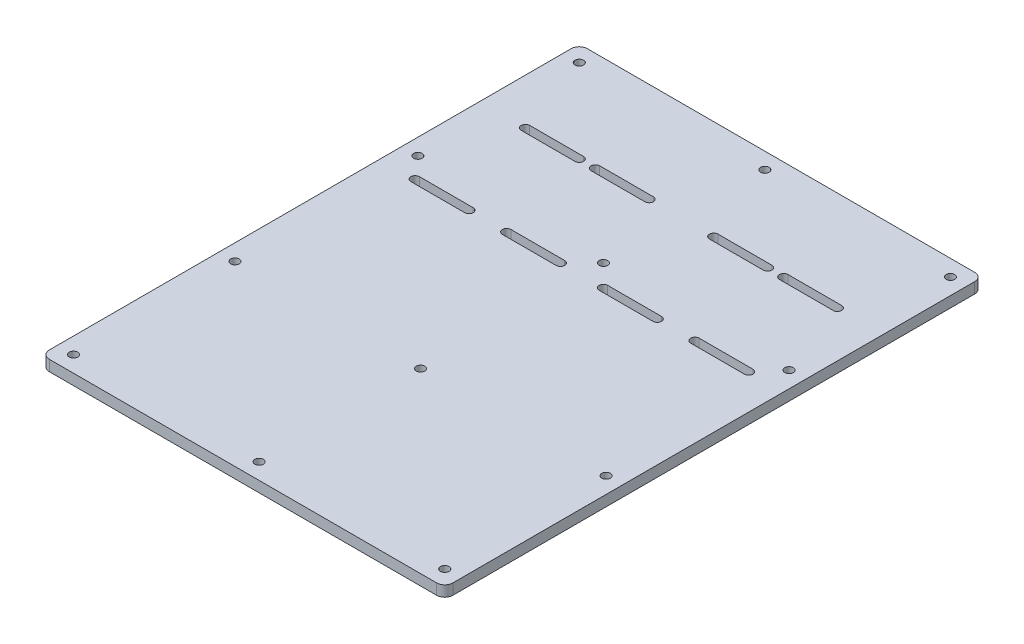
SolidWorks part; units mm, degrees
ref_plane "Front" through (0, 0, 0) normal (0, 0, 1) x (1, 0, 0)
ref_plane "Top" through (0, 0, 0) normal (0, 1, 0) x (1, 0, 0)
ref_plane "Right" through (0, 0, 0) normal (1, 0, 0) x (0, 0, -1)
sketch "Эскиз1" plane through (0, 0, 0) normal (0, 1, 0) x (1, 0, 0)
  line L1 (-72, 100) -> (72, 100)
  line L2 (-75, 97) -> (-75, -97)
  line L3 (-72, -100) -> (72, -100)
  line L4 (75, 97) -> (75, -97)
  line L5 (-75, 100) -> (75, -100) construction
  line L6 (-75, -100) -> (75, 100) construction
  arc A0 (75, -97) -> (72, -100) centre (72, -97) cw
  arc A1 (-72, -100) -> (-75, -97) centre (-72, -97) cw
  arc A2 (75, 97) -> (72, 100) centre (72, 97) ccw
  arc A3 (-72, 100) -> (-75, 97) centre (-72, 97) ccw
  point P0 (0, 0)
  dimension "D1" = 3
extrude "Бобышка-Вытянуть1" add sketch "Эскиз1" along normal blind 4
sketch "Эскиз2" plane through (0, 4, 0) normal (0, 1, 0) x (1, 0, 0)
  line L0 (-32, 64.5875) -> (-12, 64.5875)
  line L1 (0, 100) -> (0, -100) construction
  line L2 (72, 100) -> (-72, 100) construction
  line L3 (-72, -100) -> (72, -100) construction
  line L6 (-32, 61.4125) -> (-12, 61.4125)
  line L7 (-58, 64.5875) -> (-38, 64.5875)
  line L8 (-58, 61.4125) -> (-38, 61.4125)
  line L9 (-28, 27.5875) -> (-8, 27.5875)
  line L10 (-28, 24.4125) -> (-8, 24.4125)
  line L12 (-62, 27.5875) -> (-42, 27.5875)
  line L13 (-62, 24.4125) -> (-42, 24.4125)
  line L14 (62, 24.4125) -> (42, 24.4125)
  line L15 (62, 27.5875) -> (42, 27.5875)
  line L16 (28, 24.4125) -> (8, 24.4125)
  line L17 (28, 27.5875) -> (8, 27.5875)
  line L18 (58, 61.4125) -> (38, 61.4125)
  line L19 (58, 64.5875) -> (38, 64.5875)
  line L20 (32, 61.4125) -> (12, 61.4125)
  line L21 (32, 64.5875) -> (12, 64.5875)
  arc A0 (-28, 27.5875) -> (-28, 24.4125) centre (-28, 26) ccw
  arc A1 (-58, 64.5875) -> (-58, 61.4125) centre (-58, 63) ccw
  arc A2 (-62, 27.5875) -> (-62, 24.4125) centre (-62, 26) ccw
  arc A3 (-32, 64.5875) -> (-32, 61.4125) centre (-32, 63) ccw
  arc A4 (42, 24.4125) -> (42, 27.5875) centre (42, 26) cw
  arc A5 (8, 24.4125) -> (8, 27.5875) centre (8, 26) cw
  arc A6 (38, 61.4125) -> (38, 64.5875) centre (38, 63) cw
  arc A7 (12, 61.4125) -> (12, 64.5875) centre (12, 63) cw
  arc A8 (32, 64.5875) -> (32, 61.4125) centre (32, 63) cw
  arc A9 (62, 27.5875) -> (62, 24.4125) centre (62, 26) cw
  arc A10 (58, 64.5875) -> (58, 61.4125) centre (58, 63) cw
  arc A11 (28, 27.5875) -> (28, 24.4125) centre (28, 26) cw
  arc A36 (-12, 61.4125) -> (-12, 64.5875) centre (-12, 63) ccw
  arc A37 (-38, 61.4125) -> (-38, 64.5875) centre (-38, 63) ccw
  arc A38 (-8, 24.4125) -> (-8, 27.5875) centre (-8, 26) ccw
  arc A39 (-42, 24.4125) -> (-42, 27.5875) centre (-42, 26) ccw
  point P9 (0, 40)
sketch "Эскиз3" plane through (0, 4, 0) normal (0, 1, 0) x (1, 0, 0)
  line L0 (-75, 0) -> (75, 0) construction
  line L2 (0, 94) -> (-69, 94) construction
  line L3 (0, 94) -> (69, 94) construction
  line L4 (-75, 97) -> (-75, -97) construction
  line L5 (75, -97) -> (75, 97) construction
  line L6 (0, -34) -> (69, -34) construction
  line L7 (0, 34) -> (-69, 34) construction
  line L9 (0, -34) -> (-69, -34) construction
  line L10 (0, 34) -> (69, 34) construction
  line L12 (0, -94) -> (69, -94) construction
  line L13 (0, -94) -> (-69, -94) construction
  circle A0 centre (-69, 94) radius 1.5875
  circle A1 centre (0, 94) radius 1.5875
  circle A2 centre (69, 94) radius 1.5875
  circle A3 centre (-69, -34) radius 1.5875
  circle A4 centre (69, -34) radius 1.5875
  circle A5 centre (0, -34) radius 1.5875
  circle A6 centre (69, -94) radius 1.5875
  circle A7 centre (0, -94) radius 1.5875
  circle A8 centre (-69, -94) radius 1.5875
  circle A11 centre (0, 34) radius 1.5875
  circle A16 centre (69, 34) radius 1.5875
  circle A17 centre (-69, 34) radius 1.5875
extrude "Вырез-Вытянуть2" cut sketch "Эскиз3" against normal through all
extrude "Вырез-Вытянуть3" cut sketch "Эскиз2" against normal through all
